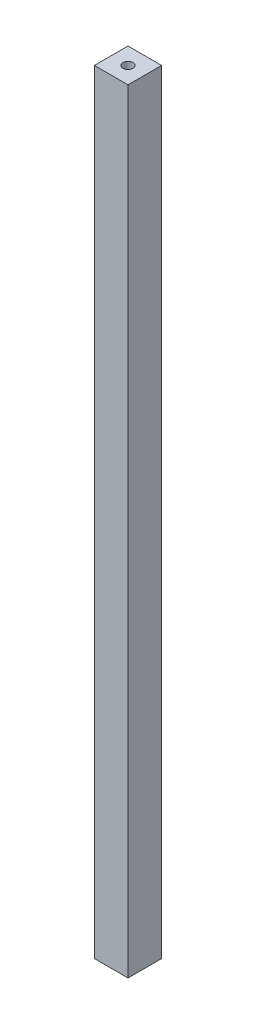
SolidWorks part; units mm, degrees
ref_plane "前视基准面" through (0, 0, 0) normal (0, 0, 1) x (1, 0, 0)
ref_plane "上视基准面" through (0, 0, 0) normal (0, 1, 0) x (1, 0, 0)
ref_plane "右视基准面" through (0, 0, 0) normal (1, 0, 0) x (0, 0, -1)
other "Configuration Table"
sketch "草图1" plane through (0, 0, 0) normal (0, 0, 1) x (1, 0, 0)
  line L0 (0, 0) -> (20, 0)
  line L1 (20, 0) -> (20, 460)
  line L2 (20, 460) -> (0, 460)
  line L3 (0, 460) -> (0, 0)
extrude "凸台-拉伸1" add sketch "草图1" along normal blind 20
sketch "草图2" plane through (0, 460, 0) normal (0, 1, 0) x (1, 0, 0)
  line L0 (0, -10) -> (20, -10)
  line L1 (0, -20) -> (0, 0) construction
  line L2 (20, -20) -> (20, 0) construction
  circle A0 centre (10, -10) radius 3
extrude "切除-拉伸1" cut sketch "草图2" against normal blind 400 contours L0 A0 | L0 A0
sketch "草图3" plane through (0, 0, 0) normal (0, -1, 0) x (1, 0, 0)
  line L0 (20, 10) -> (0, 10)
  line L1 (20, 20) -> (20, 0) construction
  line L2 (0, 20) -> (0, 0) construction
  circle A0 centre (10, 10) radius 1.8458
hole_wizard "M8 螺纹孔1" positions "草图4" profile "草图5" tap size "M8" standard "GB"
sketch "草图4" plane through (0, 0, 0) normal (0, -1, 0) x (-1, 0, 0)
  point P0 (-10, -10)
sketch "草图5" plane through (10, 0, 10) normal (1, 0, 0) x (0, 0, -1)
  line L0 (0, 0) -> (0, 21.7929)
  line L1 (0, 21.7929) -> (3.4, 19.75)
  line L2 (3.4, 19.75) -> (3.4, 0)
  line L5 (3.4, 0) -> (0, 0)
  line L10 (0, 21.7929) -> (-3.4, 19.75) construction
  line L11 (0, -6.35) -> (0, 107.95) construction
  dimension "螺纹孔钻头直径" = 6.8
  dimension "螺纹孔钻头深度" = 19.75
  dimension "导头角度" = 118
cosmetic thread "孔螺蚊线1" parameters "D1"=16, "D2"=8
